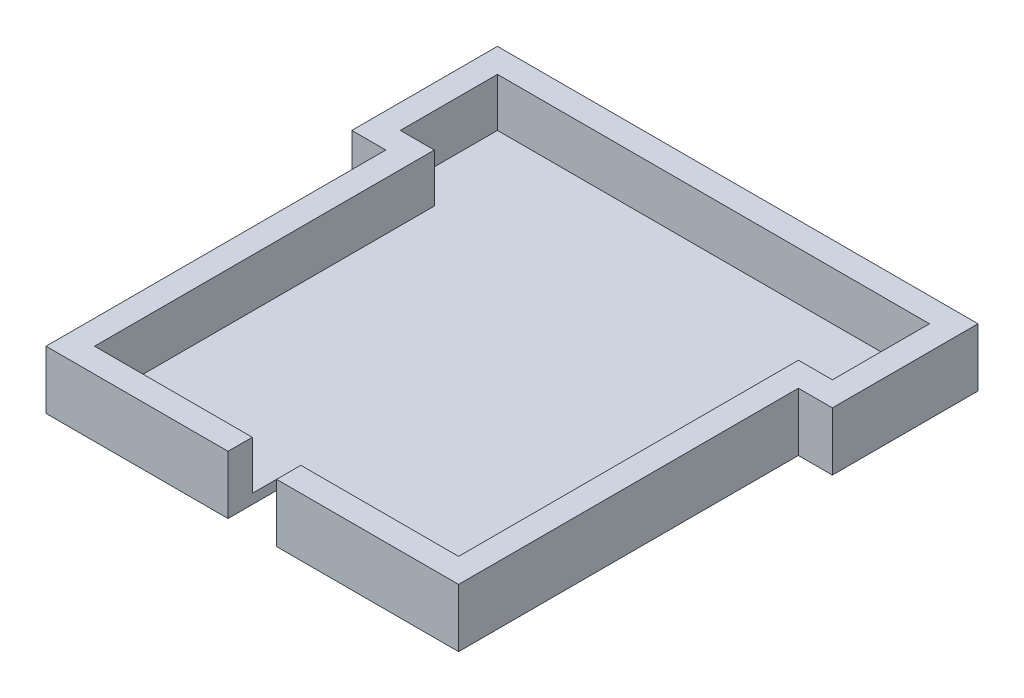
SolidWorks part; units mm, degrees
ref_plane "Front Plane" through (0, 0, 0) normal (0, 0, 1) x (1, 0, 0)
ref_plane "Top Plane" through (0, 0, 0) normal (0, 1, 0) x (1, 0, 0)
ref_plane "Right Plane" through (0, 0, 0) normal (1, 0, 0) x (0, 0, -1)
sketch "Sketch1" plane through (0, 0, 0) normal (0, 1, 0) x (1, 0, 0)
  line L0 (30.5836, 95.111) -> (23.5836, 95.111)
  line L2 (30.5836, 95.111) -> (30.5836, 25.111)
  line L3 (30.5836, 25.111) -> (105.5836, 25.111)
  line L4 (105.5836, 95.111) -> (105.5836, 25.111)
  line L5 (105.5836, 95.111) -> (112.5836, 95.111) construction
  line L6 (112.5836, 95.111) -> (112.5836, 115.111) construction
  line L7 (25.5836, 90.111) -> (25.5836, 20.111)
  line L8 (112.5836, 115.111) -> (23.5836, 115.111)
  line L9 (112.5836, 115.111) -> (112.5836, 95.111)
  line L10 (112.5836, 95.111) -> (105.5836, 95.111)
  line L11 (23.5836, 115.111) -> (23.5836, 95.111)
  line L12 (25.5836, 20.111) -> (110.5836, 20.111)
  line L13 (110.5836, 90.111) -> (110.5836, 20.111)
  line L14 (117.5836, 90.111) -> (110.5836, 90.111)
  line L15 (117.5836, 120.111) -> (117.5836, 90.111)
  line L16 (117.5836, 120.111) -> (18.5836, 120.111)
  line L17 (18.5836, 120.111) -> (18.5836, 90.111)
  line L18 (25.5836, 90.111) -> (18.5836, 90.111)
  dimension "D1" = 5
extrude "Boss-Extrude2" add sketch "Sketch1" along normal blind 2 contours L2 L3 L4 L10 L9 L8 L11 L0
sketch "Sketch3" plane through (0, 0, 0) normal (0, 1, 0) x (1, 0, 0)
  line L0 (30.5836, 95.111) -> (23.5836, 95.111)
  line L2 (30.5836, 95.111) -> (30.5836, 25.111)
  line L3 (30.5836, 25.111) -> (105.5836, 25.111)
  line L4 (105.5836, 95.111) -> (105.5836, 25.111)
  line L5 (105.5836, 95.111) -> (112.5836, 95.111) construction
  line L6 (112.5836, 95.111) -> (112.5836, 115.111) construction
  line L7 (25.5836, 90.111) -> (25.5836, 20.111)
  line L8 (112.5836, 115.111) -> (23.5836, 115.111)
  line L9 (112.5836, 115.111) -> (112.5836, 95.111)
  line L10 (112.5836, 95.111) -> (105.5836, 95.111)
  line L11 (23.5836, 115.111) -> (23.5836, 95.111)
  line L12 (25.5836, 20.111) -> (110.5836, 20.111)
  line L13 (110.5836, 90.111) -> (110.5836, 20.111)
  line L14 (117.5836, 90.111) -> (110.5836, 90.111)
  line L15 (117.5836, 120.111) -> (117.5836, 90.111)
  line L16 (117.5836, 120.111) -> (18.5836, 120.111)
  line L17 (18.5836, 120.111) -> (18.5836, 90.111)
  line L18 (25.5836, 90.111) -> (18.5836, 90.111)
  dimension "D1" = 5
extrude "Boss-Extrude3" add sketch "Sketch3" along normal blind 12
sketch "Sketch4" plane through (0, 0, -20.111) normal (0, 0, 1) x (1, 0, 0)
  line L0 (68.0836, 0) -> (63.0836, 0) construction
  line L1 (25.5836, 0) -> (110.5836, 0) construction
  line L2 (68.0836, 0) -> (73.0836, 0) construction
  line L3 (25.5836, 12) -> (110.5836, 12) construction
  line L4 (63.0836, 0) -> (73.0836, 0)
  line L5 (63.0836, 0) -> (63.0836, 12)
  line L6 (63.0836, 12) -> (73.0836, 12)
  line L7 (73.0836, 0) -> (73.0836, 12)
extrude "Cut-Extrude1" cut sketch "Sketch4" against normal blind 12 contours L5 L4 L7 L6
